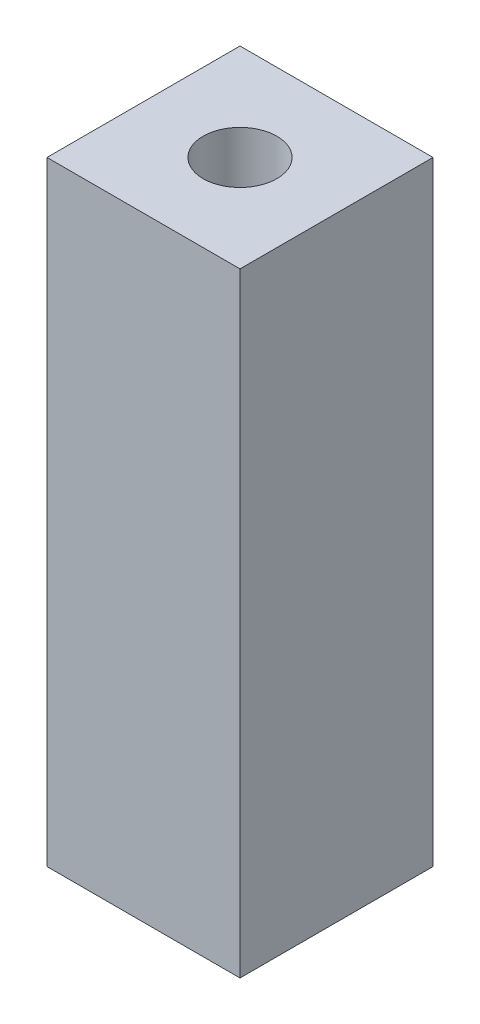
SolidWorks part; units mm, degrees
ref_plane "Front Plane" through (0, 0, 0) normal (0, 0, 1) x (1, 0, 0)
ref_plane "Top Plane" through (0, 0, 0) normal (0, 1, 0) x (1, 0, 0)
ref_plane "Right Plane" through (0, 0, 0) normal (1, 0, 0) x (0, 0, -1)
sketch "Sketch1" plane through (0, 0, 0) normal (0, 1, 0) x (1, 0, 0)
  line L1 (-5.5, 5.5) -> (5.5, 5.5)
  line L2 (-5.5, 5.5) -> (-5.5, -5.5)
  line L3 (-5.5, -5.5) -> (5.5, -5.5)
  line L4 (5.5, 5.5) -> (5.5, -5.5)
  line L5 (-5.5, 5.5) -> (5.5, -5.5) construction
  line L6 (-5.5, -5.5) -> (5.5, 5.5) construction
  point P0 (0, 0)
  dimension "D1" = 11
extrude "Boss-Extrude1" add sketch "Sketch1" along normal blind 35
hole_wizard "M5x0.8 Tapped Hole1" positions "Sketch2" profile "Sketch3" tap size "M5x0.8" standard "ANSI Metric" end condition through all
sketch "Sketch2" plane through (0, 35, 0) normal (0, 1, 0) x (1, 0, 0)
  point P0 (0, 0)
sketch "Sketch3" plane through (0, 35, 0) normal (1, 0, 0) x (0, 0, 1)
  line L0 (0, 0) -> (0, 35)
  line L1 (0, 35) -> (2.1, 35)
  line L2 (2.1, 35) -> (2.1, 0)
  line L5 (2.1, 0) -> (0, 0)
  line L11 (0, -6.35) -> (0, 107.95) construction
  dimension "Thru Tap Drill Dia." = 4.2
  dimension "Thru Tap Drill Depth" = 35
cosmetic thread "Hole Thread1" parameters "D2"=5
